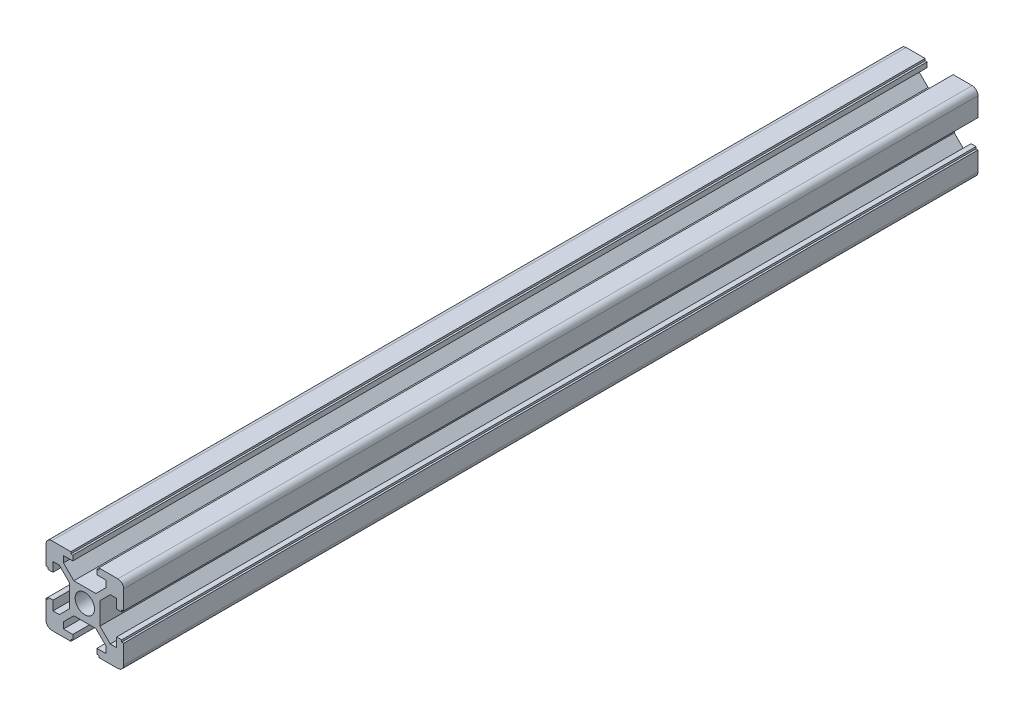
SolidWorks part; units mm, degrees
ref_plane "Front Plane" through (0, 0, 0) normal (0, 0, 1) x (1, 0, 0)
ref_plane "Top Plane" through (0, 0, 0) normal (0, 1, 0) x (1, 0, 0)
ref_plane "Right Plane" through (0, 0, 0) normal (1, 0, 0) x (0, 0, -1)
sketch "Sketch1" plane through (0, 0, 0) normal (0, 0, 1) x (1, 0, 0)
  line L0 (0, 13.3843) -> (0, -12.9126) construction
  line L1 (-14.4653, 0) -> (14.4653, 0) construction
  line L2 (2.8393, 3.9) -> (5.5, 6.5607)
  line L3 (-8.5, 10) -> (-3.6, 10)
  line L4 (-10, 8.5) -> (-10, 3.6)
  line L5 (-8.5, -10) -> (-3.6, -10)
  line L6 (10, 8.5) -> (10, 3.6)
  line L7 (-10, 10) -> (10, -10) construction
  line L8 (-10, -10) -> (10, 10) construction
  line L9 (-5.5, 8.2) -> (-3.1, 8.2)
  line L10 (-5.9626, 4.902) -> (-4.902, 5.9626) construction
  line L11 (-2.8393, 3.9) -> (-5.5, 6.5607)
  line L12 (-5.5, 8.2) -> (-5.5, 6.5607)
  line L13 (-2.8393, 3.9) -> (2.8393, 3.9)
  line L14 (5.5, 8.2) -> (5.5, 6.5607)
  line L15 (-3.1, 9.5) -> (-3.1, 8.2)
  line L16 (3.1, 9.5) -> (3.1, 8.2)
  line L17 (-3.1, 9.5) -> (3.1, 9.5) construction
  line L18 (-3.1, 9.5) -> (-3.6, 9.5)
  line L19 (-3.6, 9.5) -> (-3.6, 10)
  line L20 (3.1, 9.5) -> (3.6, 9.5)
  line L21 (3.6, 9.5) -> (3.6, 10)
  line L22 (3.6, 10) -> (8.5, 10)
  line L23 (3.1, 8.2) -> (5.5, 8.2)
  line L24 (-9.5, -3.1) -> (-9.5, -3.6)
  line L25 (-9.5, -3.6) -> (-10, -3.6)
  line L26 (-9.5, -3.1) -> (-8.2, -3.1)
  line L27 (-8.2, -3.1) -> (-8.2, -5.5)
  line L28 (-8.2, -5.5) -> (-6.5607, -5.5)
  line L29 (-3.9, -2.8393) -> (-6.5607, -5.5)
  line L30 (-3.9, 2.8393) -> (-3.9, -2.8393)
  line L31 (-3.9, 2.8393) -> (-6.5607, 5.5)
  line L32 (-8.2, 5.5) -> (-6.5607, 5.5)
  line L33 (-8.2, 5.5) -> (-8.2, 3.1)
  line L34 (-9.5, 3.1) -> (-8.2, 3.1)
  line L35 (-9.5, 3.1) -> (-9.5, 3.6)
  line L36 (-9.5, 3.6) -> (-10, 3.6)
  line L37 (-3.6, -9.5) -> (-3.6, -10)
  line L38 (-3.1, -9.5) -> (-3.6, -9.5)
  line L39 (-3.1, -9.5) -> (-3.1, -8.2)
  line L40 (-3.1, -8.2) -> (-5.5, -8.2)
  line L41 (-5.5, -8.2) -> (-5.5, -6.5607)
  line L42 (-2.8393, -3.9) -> (-5.5, -6.5607)
  line L43 (2.8393, -3.9) -> (-2.8393, -3.9)
  line L44 (2.8393, -3.9) -> (5.5, -6.5607)
  line L45 (5.5, -8.2) -> (5.5, -6.5607)
  line L46 (5.5, -8.2) -> (3.1, -8.2)
  line L47 (3.1, -9.5) -> (3.6, -9.5)
  line L48 (3.1, -9.5) -> (3.1, -8.2)
  line L49 (3.6, -9.5) -> (3.6, -10)
  line L50 (9.5, -3.6) -> (10, -3.6)
  line L51 (9.5, -3.1) -> (9.5, -3.6)
  line L52 (9.5, -3.1) -> (8.2, -3.1)
  line L53 (8.2, -5.5) -> (8.2, -3.1)
  line L54 (8.2, -5.5) -> (6.5607, -5.5)
  line L55 (3.9, -2.8393) -> (6.5607, -5.5)
  line L56 (3.9, -2.8393) -> (3.9, 2.8393)
  line L57 (3.9, 2.8393) -> (6.5607, 5.5)
  line L58 (8.2, 5.5) -> (6.5607, 5.5)
  line L59 (8.2, 3.1) -> (8.2, 5.5)
  line L60 (9.5, 3.1) -> (8.2, 3.1)
  line L61 (9.5, 3.1) -> (9.5, 3.6)
  line L62 (9.5, 3.6) -> (10, 3.6)
  line L63 (-10, -3.6) -> (-10, -8.5)
  line L64 (3.6, -10) -> (8.5, -10)
  line L65 (10, -3.6) -> (10, -8.5)
  arc A0 (8.5, 10) -> (10, 8.5) centre (8.5, 8.5) cw
  arc A1 (8.5, -10) -> (10, -8.5) centre (8.5, -8.5) ccw
  arc A2 (-10, -8.5) -> (-8.5, -10) centre (-8.5, -8.5) ccw
  arc A3 (-8.5, 10) -> (-10, 8.5) centre (-8.5, 8.5) ccw
  circle A4 centre (0, 0.2358) radius 2.5
  point P5 (0, 0)
  point P30 (-5.4323, 5.4323)
  point P38 (0, 9.5)
  dimension "D3" = 1.5
  dimension "D15" = 5
  dimension "D1" = 20
  dimension "D2" = 20
  dimension "D4" = 6.2
  dimension "D5" = 11
  dimension "D6" = 1.8
  dimension "D7" = 1.5
  dimension "D8" = 90
  dimension "D9" = 0.5
  dimension "D10" = 0.5
  dimension "D11" = 0.5
  dimension "D12" = 0.5
  dimension "D13" = 6.1
  dimension "D14" = 45
extrude "Boss-Extrude1" add sketch "Sketch1" along normal blind 220
